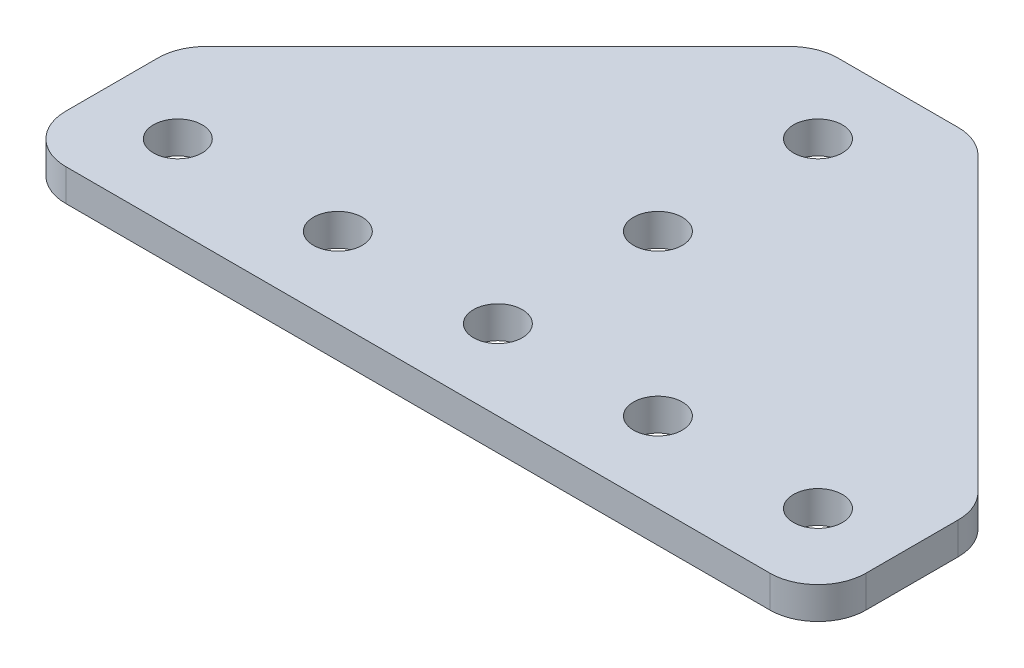
SolidWorks part; units mm, degrees
ref_plane "前视基准面" through (0, 0, 0) normal (0, 0, 1) x (1, 0, 0)
ref_plane "上视基准面" through (0, 0, 0) normal (0, 1, 0) x (1, 0, 0)
ref_plane "右视基准面" through (0, 0, 0) normal (1, 0, 0) x (0, 0, -1)
other "Configuration Table"
sketch "草图1" plane through (0, 0, 0) normal (0, 1, 0) x (1, 0, 0)
  line L0 (0, 0) -> (0, 30) construction
  line L1 (-5, 30) -> (5, 30)
  line L2 (-5, 30) -> (-5, 10) construction
  line L3 (-5, 10) -> (-25, 10) construction
  line L4 (-25, 10) -> (-25, 0)
  line L5 (-25, 0) -> (25, 0)
  line L6 (25, 10) -> (25, 0)
  line L7 (5, 10) -> (25, 10) construction
  line L8 (5, 30) -> (5, 10) construction
  line L9 (10, 5) -> (25, 5) construction
  line L10 (-25, 10) -> (-5, 30)
  line L11 (5, 30) -> (25, 10)
  circle A0 centre (0, 25) radius 1.525
  circle A1 centre (0, 15) radius 1.525
  circle A2 centre (0, 5) radius 1.525
  circle A3 centre (10, 5) radius 1.525
  circle A4 centre (-10, 5) radius 1.525
  circle A5 centre (20, 5) radius 1.525
  circle A6 centre (-20, 5) radius 1.525
  dimension "D9" = 3.05
  dimension "D1" = 20
  dimension "D2" = 50
  dimension "D3" = 10
  dimension "D4" = 10
  dimension "D5" = 10
  dimension "D6" = 10
  dimension "D7" = 10
  dimension "D8" = 10
  dimension "D10" = 10
  dimension "D11" = 10
extrude "凸台-拉伸1" add sketch "草图1" along normal blind 2
fillet "圆角1" radius 3 6 edges at (-25, 1, 0) (25, 1, 0) (-5, 1, -30) (5, 1, -30) (25, 1, -10) (-25, 1, -10)
